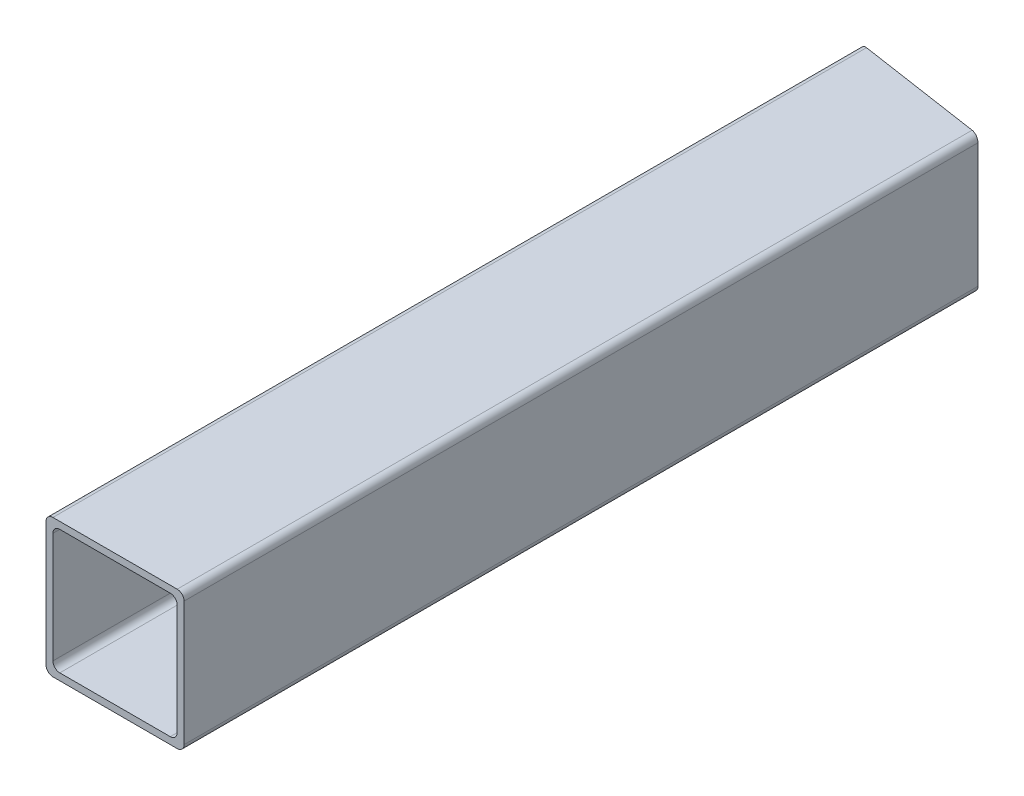
SolidWorks part; units mm, degrees
ref_plane "Спереди" through (0, 0, 0) normal (0, 0, 1) x (1, 0, 0)
ref_plane "Сверху" through (0, 0, 0) normal (0, 1, 0) x (1, 0, 0)
ref_plane "Справа" through (0, 0, 0) normal (1, 0, 0) x (0, 0, -1)
sketch "Эскиз1" plane through (0, 0, 0) normal (0, 0, 1) x (1, 0, 0)
  line L1 (-18, 20) -> (18, 20)
  line L2 (-20, 18) -> (-20, -18)
  line L3 (-18, -20) -> (18, -20)
  line L4 (20, 18) -> (20, -18)
  line L5 (-20, 20) -> (20, -20) construction
  line L6 (-20, -20) -> (20, 20) construction
  line L7 (-16, 18) -> (16, 18)
  line L8 (-18, 16) -> (-18, -16)
  line L9 (-16, -18) -> (16, -18)
  line L10 (18, 16) -> (18, -16)
  line L11 (-18, 18) -> (18, -18) construction
  line L12 (-18, -18) -> (18, 18) construction
  arc A0 (18, 20) -> (20, 18) centre (18, 18) cw
  arc A1 (16, 18) -> (18, 16) centre (16, 16) cw
  arc A2 (18, -20) -> (20, -18) centre (18, -18) ccw
  arc A3 (16, -18) -> (18, -16) centre (16, -16) ccw
  arc A4 (-20, -18) -> (-18, -20) centre (-18, -18) ccw
  arc A5 (-18, -16) -> (-16, -18) centre (-16, -16) ccw
  arc A6 (-16, 18) -> (-18, 16) centre (-16, 16) ccw
  arc A7 (-18, 20) -> (-20, 18) centre (-18, 18) ccw
  point P0 (0, 0)
  point P6 (0, 0)
  dimension "D5" = 2
  dimension "D1" = 40
  dimension "D2" = 40
  dimension "D3" = 2
  dimension "D4" = 2
extrude "Бобышка-Вытянуть1" add sketch "Эскиз1" along normal blind 236
sketch "Эскиз2" plane through (0, 20, 0) normal (0, 1, 0) x (1, 0, 0)
  line L3 (20, -236) -> (20, 0) construction
  line L4 (20, -6) -> (-20, 0)
  line L6 (20, -6) -> (20, 0)
  line L7 (20, 0) -> (-20, 0)
  line L8 (18, -236) -> (-18, -236) construction
  dimension "D1" = 230
extrude "Вырез-Вытянуть1" cut sketch "Эскиз2" against normal through all
